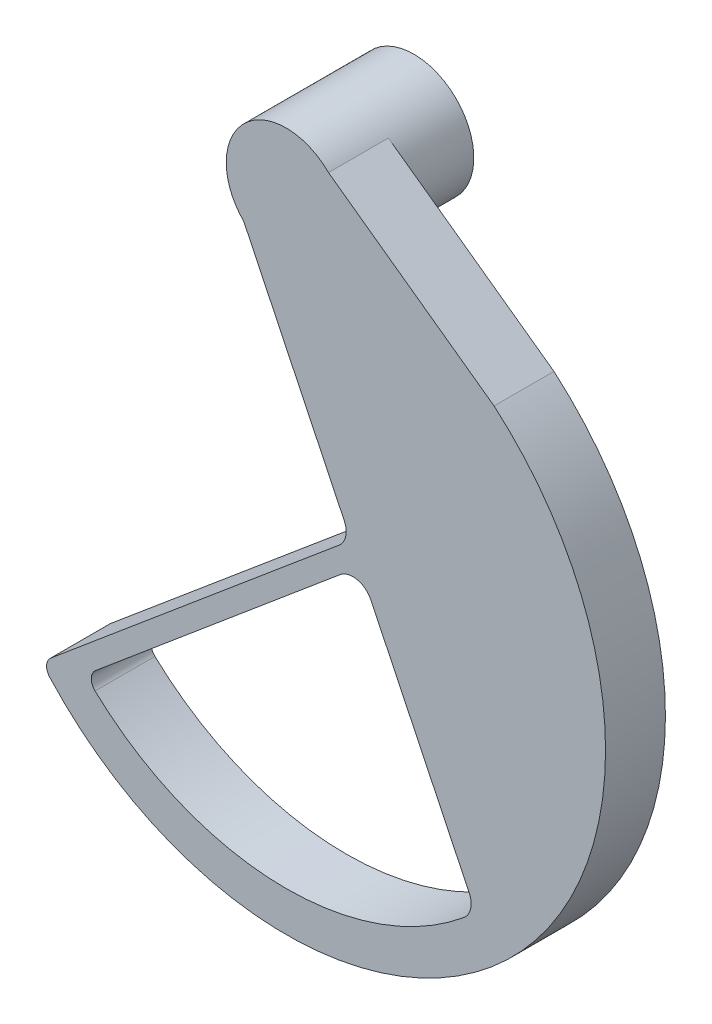
SolidWorks part; units mm, degrees
ref_plane "正面" through (0, 0, 0) normal (0, 0, 1) x (1, 0, 0)
ref_plane "平面" through (0, 0, 0) normal (0, 1, 0) x (1, 0, 0)
ref_plane "右側面" through (0, 0, 0) normal (1, 0, 0) x (0, 0, -1)
sketch "ｽｹｯﾁ4" plane through (0, 0, 0) normal (0, 0, 1) x (1, 0, 0)
  line L0 (0, 0.7897) -> (0, 0)
  line L1 (-53.6231, -124.9951) -> (-58.9406, -129.4571)
  line L3 (-10.6066, -10.6066) -> (14.5363, -62.8896)
  line L4 (-53.6231, -124.9951) -> (13.2442, -68.8868)
  line L5 (21.2324, -76.8138) -> (45.8448, -127.9938)
  line L6 (10.6066, 10.6066) -> (52.0762, -19.2705)
  line L7 (-58.0696, -135.2532) -> (-57.9498, -135.1527)
  line L8 (-47.7477, -126.5866) -> (13.5112, -75.1515)
  arc A1 (-59.2335, -133.7716) -> (52.0762, -19.2705) centre (0, -80) ccw
  arc A2 (-47.8702, -131.073) -> (44.5187, -134.0193) centre (0, -80) ccw
  arc A3 (10.6066, 10.6066) -> (-10.6066, -10.6066) centre (0, 0) ccw
  arc A4 (-59.2335, -133.7716) -> (-58.9406, -129.4571) centre (-57.0123, -131.7552) cw
  arc A5 (-47.8702, -131.073) -> (-47.7477, -126.5866) centre (-45.8186, -128.8841) cw
  arc A6 (13.5112, -75.1515) -> (21.2324, -76.8138) centre (16.7264, -78.9807) cw
  arc A7 (13.2442, -68.8868) -> (14.5363, -62.8896) centre (10.0302, -65.0566) ccw
  arc A8 (45.8448, -127.9938) -> (44.5187, -134.0193) centre (41.3388, -130.1608) cw
  point P18 (-61.2836, -131.423)
  point P21 (-50.2744, -128.7081)
  point P24 (18.4421, -71.0114)
  dimension "D3" = 140
  dimension "D4" = 30
  dimension "D5" = 5
  dimension "D6" = 3
  dimension "D7" = 3
  dimension "D8" = 5
  dimension "D9" = 5
  dimension "D10" = 5
  dimension "D2" = 5
extrude "ﾎﾞｽ - 押し出し1" add sketch "ｽｹｯﾁ4" along normal blind 15
sketch "ｽｹｯﾁ9" plane through (0, 0, 0) normal (0, 0, -1) x (-1, 0, 0)
  circle A0 centre (0, 0) radius 15
  dimension "D1" = 30
extrude "ﾎﾞｽ - 押し出し3" add sketch "ｽｹｯﾁ9" along normal blind 17
sketch "ｽｹｯﾁ10" plane through (0, 0, -17) normal (0, 0, -1) x (-1, 0, 0)
  circle A0 centre (0, 0) radius 10
extrude "ｶｯﾄ - 押し出し4" cut sketch "ｽｹｯﾁ10" against normal blind 2
